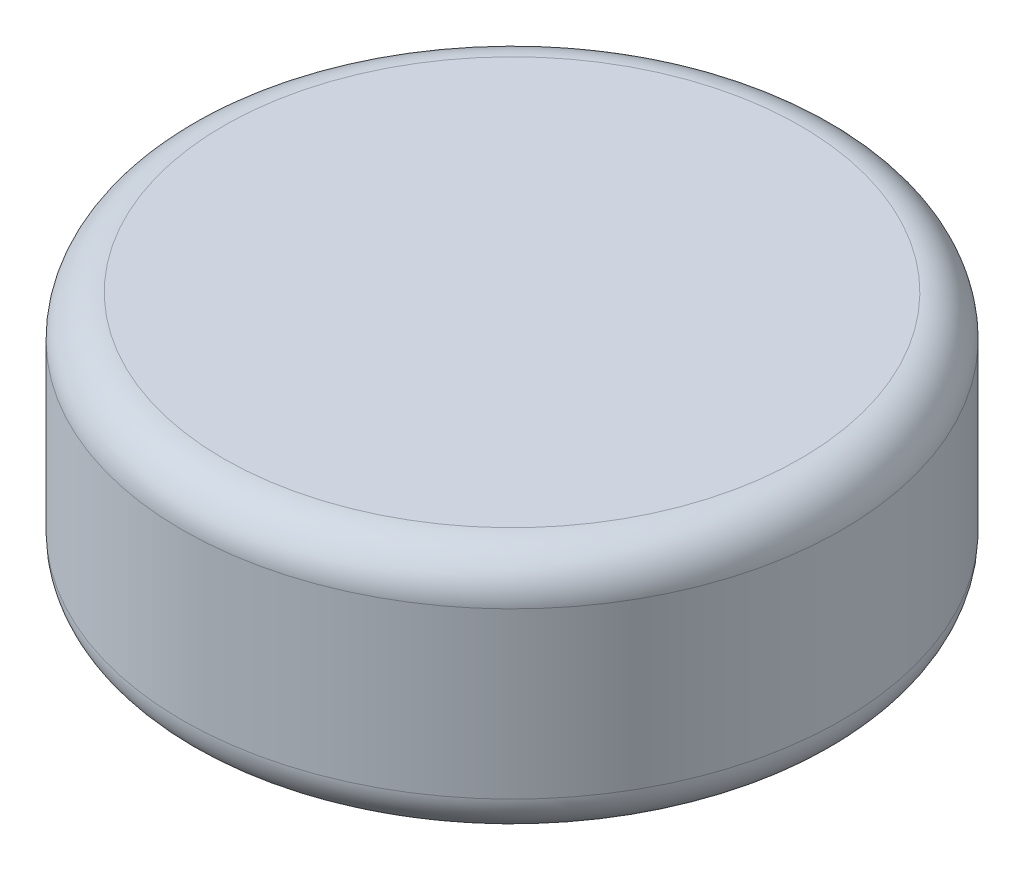
SolidWorks part; units mm, degrees
ref_plane "Front" through (0, 0, 0) normal (0, 0, 1) x (1, 0, 0)
ref_plane "Top" through (0, 0, 0) normal (0, 1, 0) x (1, 0, 0)
ref_plane "Right" through (0, 0, 0) normal (1, 0, 0) x (0, 0, -1)
sketch "Sketch1" plane through (0, 0, 0) normal (0, 1, 0) x (1, 0, 0)
  circle A0 centre (0, 0) radius 4
  dimension "D1" = 8
extrude "Boss-Extrude1" add sketch "Sketch1" along normal blind 3
fillet "Fillet1" radius 0.5 2 edges at (0, 0, 4) (0, 3, 4)
